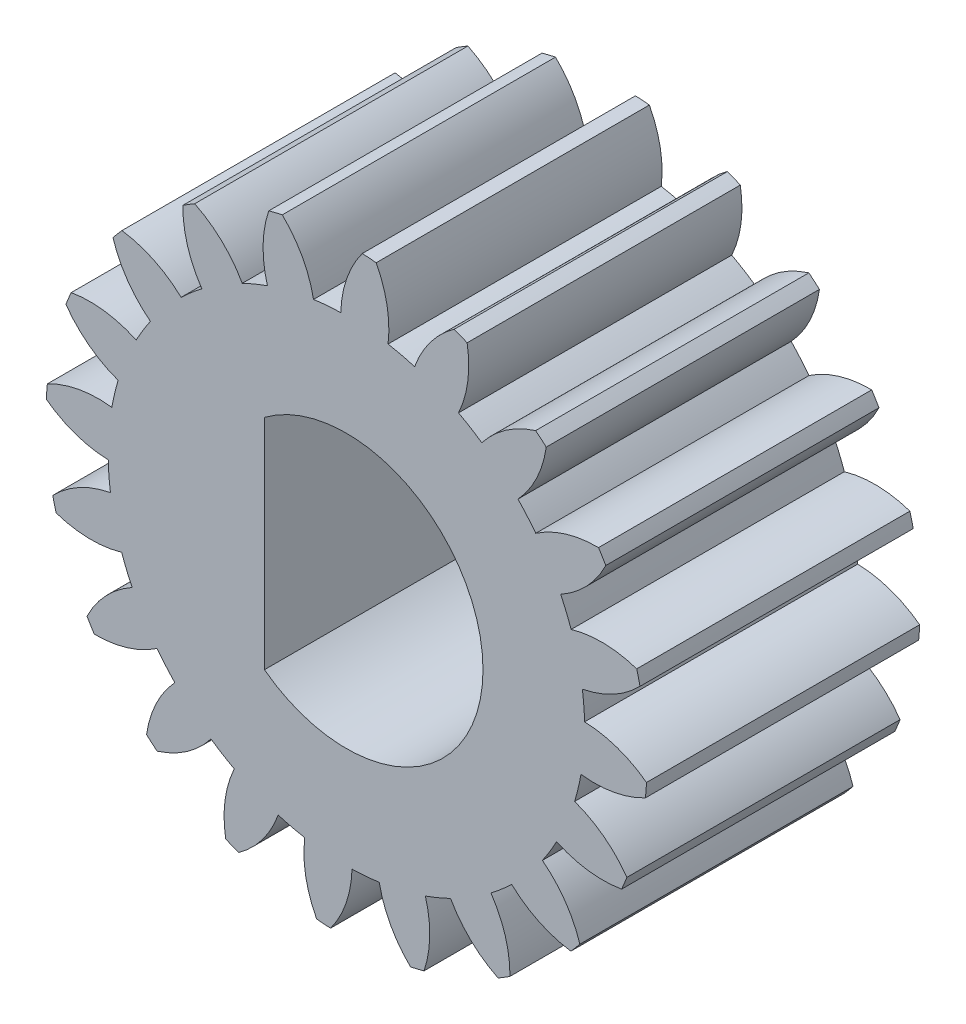
SolidWorks part; units mm, degrees
ref_plane "Front Plane" through (0, 0, 0) normal (0, 0, 1) x (1, 0, 0)
ref_plane "Top Plane" through (0, 0, 0) normal (0, 1, 0) x (1, 0, 0)
ref_plane "Right Plane" through (0, 0, 0) normal (1, 0, 0) x (0, 0, -1)
sketch "Sketch1" plane through (0, 0, 0) normal (0, 0, 1) x (1, 0, 0)
  line L0 (-1.905, 2.54) -> (-1.905, -2.54)
  arc A0 (-1.905, -2.54) -> (-1.905, 2.54) centre (0, 0) ccw
  arc B0 (5.8601, 3.8012) -> (4.4013, 3.36) centre (5.8322, 1.2614) ccw
  arc B1 (4.4013, 3.36) -> (3.9879, 3.8415) centre (0, 0) ccw
  arc B2 (3.9879, 3.8415) -> (4.6451, 5.2166) centre (2.1303, 5.5738) ccw
  arc B3 (4.6451, 5.2166) -> (4.3986, 5.4261) centre (0, 0) ccw
  arc B4 (4.3986, 5.4261) -> (3.1476, 4.5556) centre (5.157, 3.0019) ccw
  arc B5 (3.1476, 4.5556) -> (2.6057, 4.8858) centre (0, 0) ccw
  arc B6 (2.6057, 4.8858) -> (2.8057, 6.3967) centre (0.3037, 5.9593) ccw
  arc B7 (2.8057, 6.3967) -> (2.5066, 6.5198) centre (0, 0) ccw
  arc B8 (2.5066, 6.5198) -> (1.5858, 5.3053) centre (3.9769, 4.4486) ccw
  arc B9 (1.5858, 5.3053) -> (0.9683, 5.4519) centre (0, 0) ccw
  arc B10 (0.9683, 5.4519) -> (0.6917, 6.9507) centre (-1.5527, 5.7615) ccw
  arc B11 (0.6917, 6.9507) -> (0.3692, 6.9752) centre (0, 0) ccw
  arc B12 (0.3692, 6.9752) -> (-0.1313, 5.5356) centre (2.4076, 5.4598) ccw
  arc B13 (-0.1313, 5.5356) -> (-0.7638, 5.4843) centre (0, 0) ccw
  arc B14 (-0.7638, 5.4843) -> (-1.49, 6.8242) centre (-3.2571, 4.9997) ccw
  arc B15 (-1.49, 6.8242) -> (-1.8043, 6.7479) centre (0, 0) ccw
  arc B16 (-1.8043, 6.7479) -> (-1.8355, 5.2241) centre (0.6026, 5.9365) ccw
  arc B17 (-1.8355, 5.2241) -> (-2.4211, 4.9798) centre (0, 0) ccw
  arc B18 (-2.4211, 4.9798) -> (-3.5259, 6.0298) centre (-4.6427, 3.7485) ccw
  arc B19 (-3.5259, 6.0298) -> (-3.8012, 5.8601) centre (0, 0) ccw
  arc B20 (-3.8012, 5.8601) -> (-3.36, 4.4013) centre (-1.2614, 5.8322) ccw
  arc B21 (-3.36, 4.4013) -> (-3.8415, 3.9879) centre (0, 0) ccw
  arc B22 (-3.8415, 3.9879) -> (-5.2166, 4.6451) centre (-5.5738, 2.1303) ccw
  arc B23 (-5.2166, 4.6451) -> (-5.4261, 4.3986) centre (0, 0) ccw
  arc B24 (-5.4261, 4.3986) -> (-4.5556, 3.1476) centre (-3.0019, 5.157) ccw
  arc B25 (-4.5556, 3.1476) -> (-4.8858, 2.6057) centre (0, 0) ccw
  arc B26 (-4.8858, 2.6057) -> (-6.3967, 2.8057) centre (-5.9593, 0.3037) ccw
  arc B27 (-6.3967, 2.8057) -> (-6.5198, 2.5066) centre (0, 0) ccw
  arc B28 (-6.5198, 2.5066) -> (-5.3053, 1.5858) centre (-4.4486, 3.9769) ccw
  arc B29 (-5.3053, 1.5858) -> (-5.4519, 0.9683) centre (0, 0) ccw
  arc B30 (-5.4519, 0.9683) -> (-6.9507, 0.6917) centre (-5.7615, -1.5527) ccw
  arc B31 (-6.9507, 0.6917) -> (-6.9752, 0.3692) centre (0, 0) ccw
  arc B32 (-6.9752, 0.3692) -> (-5.5356, -0.1313) centre (-5.4598, 2.4076) ccw
  arc B33 (-5.5356, -0.1313) -> (-5.4843, -0.7638) centre (0, 0) ccw
  arc B34 (-5.4843, -0.7638) -> (-6.8242, -1.49) centre (-4.9997, -3.2571) ccw
  arc B35 (-6.8242, -1.49) -> (-6.7479, -1.8043) centre (0, 0) ccw
  arc B36 (-6.7479, -1.8043) -> (-5.2241, -1.8355) centre (-5.9365, 0.6026) ccw
  arc B37 (-5.2241, -1.8355) -> (-4.9798, -2.4211) centre (0, 0) ccw
  arc B38 (-4.9798, -2.4211) -> (-6.0298, -3.5259) centre (-3.7485, -4.6427) ccw
  arc B39 (-6.0298, -3.5259) -> (-5.8601, -3.8012) centre (0, 0) ccw
  arc B40 (-5.8601, -3.8012) -> (-4.4013, -3.36) centre (-5.8322, -1.2614) ccw
  arc B41 (-4.4013, -3.36) -> (-3.9879, -3.8415) centre (0, 0) ccw
  arc B42 (-3.9879, -3.8415) -> (-4.6451, -5.2166) centre (-2.1303, -5.5738) ccw
  arc B43 (-4.6451, -5.2166) -> (-4.3986, -5.4261) centre (0, 0) ccw
  arc B44 (-4.3986, -5.4261) -> (-3.1476, -4.5556) centre (-5.157, -3.0019) ccw
  arc B45 (-3.1476, -4.5556) -> (-2.6057, -4.8858) centre (0, 0) ccw
  arc B46 (-2.6057, -4.8858) -> (-2.8057, -6.3967) centre (-0.3037, -5.9593) ccw
  arc B47 (-2.8057, -6.3967) -> (-2.5066, -6.5198) centre (0, 0) ccw
  arc B48 (-2.5066, -6.5198) -> (-1.5858, -5.3053) centre (-3.9769, -4.4486) ccw
  arc B49 (-1.5858, -5.3053) -> (-0.9683, -5.4519) centre (0, 0) ccw
  arc B50 (-0.9683, -5.4519) -> (-0.6917, -6.9507) centre (1.5527, -5.7615) ccw
  arc B51 (-0.6917, -6.9507) -> (-0.3692, -6.9752) centre (0, 0) ccw
  arc B52 (-0.3692, -6.9752) -> (0.1313, -5.5356) centre (-2.4076, -5.4598) ccw
  arc B53 (0.1313, -5.5356) -> (0.7638, -5.4843) centre (0, 0) ccw
  arc B54 (0.7638, -5.4843) -> (1.49, -6.8242) centre (3.2571, -4.9997) ccw
  arc B55 (1.49, -6.8242) -> (1.8043, -6.7479) centre (0, 0) ccw
  arc B56 (1.8043, -6.7479) -> (1.8355, -5.2241) centre (-0.6026, -5.9365) ccw
  arc B57 (1.8355, -5.2241) -> (2.4211, -4.9798) centre (0, 0) ccw
  arc B58 (2.4211, -4.9798) -> (3.5259, -6.0298) centre (4.6427, -3.7485) ccw
  arc B59 (3.5259, -6.0298) -> (3.8012, -5.8601) centre (0, 0) ccw
  arc B60 (3.8012, -5.8601) -> (3.36, -4.4013) centre (1.2614, -5.8322) ccw
  arc B61 (3.36, -4.4013) -> (3.8415, -3.9879) centre (0, 0) ccw
  arc B62 (3.8415, -3.9879) -> (5.2166, -4.6451) centre (5.5738, -2.1303) ccw
  arc B63 (5.2166, -4.6451) -> (5.4261, -4.3986) centre (0, 0) ccw
  arc B64 (5.4261, -4.3986) -> (4.5556, -3.1476) centre (3.0019, -5.157) ccw
  arc B65 (4.5556, -3.1476) -> (4.8858, -2.6057) centre (0, 0) ccw
  arc B66 (4.8858, -2.6057) -> (6.3967, -2.8057) centre (5.9593, -0.3037) ccw
  arc B67 (6.3967, -2.8057) -> (6.5198, -2.5066) centre (0, 0) ccw
  arc B68 (6.5198, -2.5066) -> (5.3053, -1.5858) centre (4.4486, -3.9769) ccw
  arc B69 (5.3053, -1.5858) -> (5.4519, -0.9683) centre (0, 0) ccw
  arc B70 (5.4519, -0.9683) -> (6.9507, -0.6917) centre (5.7615, 1.5527) ccw
  arc B71 (6.9507, -0.6917) -> (6.9752, -0.3692) centre (0, 0) ccw
  arc B72 (6.9752, -0.3692) -> (5.5356, 0.1313) centre (5.4598, -2.4076) ccw
  arc B73 (5.5356, 0.1313) -> (5.4843, 0.7638) centre (0, 0) ccw
  arc B74 (5.4843, 0.7638) -> (6.8242, 1.49) centre (4.9997, 3.2571) ccw
  arc B75 (6.8242, 1.49) -> (6.7479, 1.8043) centre (0, 0) ccw
  arc B76 (6.7479, 1.8043) -> (5.2241, 1.8355) centre (5.9365, -0.6026) ccw
  arc B77 (5.2241, 1.8355) -> (4.9798, 2.4211) centre (0, 0) ccw
  arc B78 (4.9798, 2.4211) -> (6.0298, 3.5259) centre (3.7485, 4.6427) ccw
  arc B79 (6.0298, 3.5259) -> (5.8601, 3.8012) centre (0, 0) ccw
  dimension "D1" = 6.35
  dimension "D2" = 1.905
sketch_block_instance "Idler_Gear-1"
sketch_block "Idler_Gear"
extrude "Boss-Extrude1" add sketch "Sketch1" along normal blind 6.35
